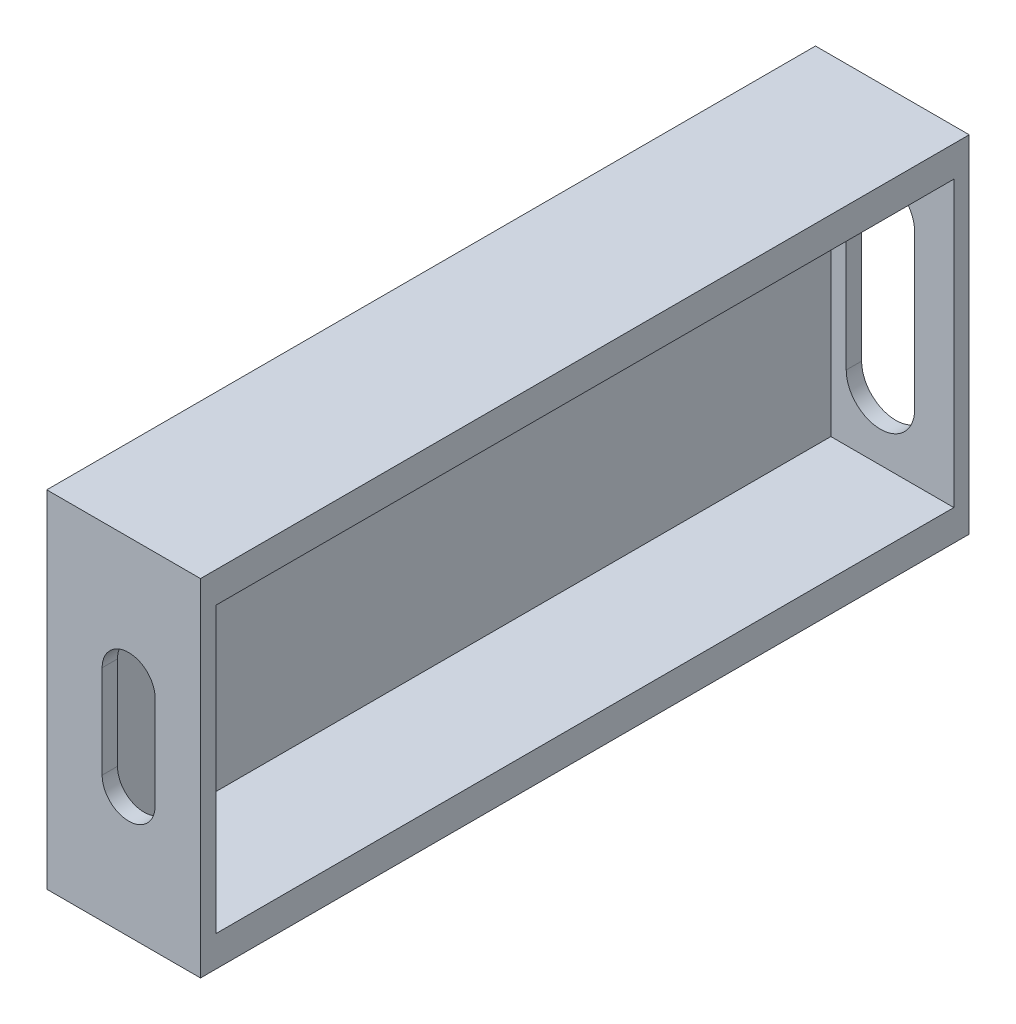
SolidWorks part; units mm, degrees
ref_plane "Front Plane" through (0, 0, 0) normal (0, 0, 1) x (1, 0, 0)
ref_plane "Top Plane" through (0, 0, 0) normal (0, 1, 0) x (1, 0, 0)
ref_plane "Right Plane" through (0, 0, 0) normal (1, 0, 0) x (0, 0, -1)
sketch "Sketch2" plane through (0, 0, 0) normal (1, 0, 0) x (0, 0, -1)
  line L1 (0, 0) -> (50, 0)
  line L2 (0, 0) -> (0, 22.5)
  line L3 (0, 22.5) -> (50, 22.5)
  line L4 (50, 0) -> (50, 22.5)
  dimension "D1" = 50
  dimension "D2" = 22.5
extrude "Boss-Extrude1" add sketch "Sketch2" along normal blind 10 contours L2 L3 L4 L1
sketch "Sketch4" plane through (0, 0, 0) normal (0, 0, 1) x (1, 0, 0)
  line L0 (5.325, 14.275) -> (5.325, 8.225) construction
  line L1 (7.05, 14.275) -> (7.05, 8.225)
  line L2 (3.6, 14.275) -> (3.6, 8.225)
  line L3 (0, 0) -> (0, 22.5) construction
  arc A0 (7.05, 14.275) -> (3.6, 14.275) centre (5.325, 14.275) ccw
  arc A1 (3.6, 8.225) -> (7.05, 8.225) centre (5.325, 8.225) ccw
  point P2 (5.325, 11.25)
  point P7 (3.6, 11.25)
  point P10 (0, 11.25)
  point P11 (5.325, 16)
  point P12 (5.325, 6.5)
  dimension "D3" = 3.45
  dimension "D4" = 9.5
  dimension "D1" = 0
  dimension "D2" = 3.6
extrude "USBC" cut sketch "Sketch4" against normal blind 10
sketch "Sketch5" plane through (0, 0, -50) normal (0, 0, -1) x (-1, 0, 0)
  line L0 (-5.225, 16.25) -> (-5.225, 6.25) construction
  line L1 (-3, 16.25) -> (-3, 6.25)
  line L2 (-7.45, 16.25) -> (-7.45, 6.25)
  line L3 (-10, 0) -> (-10, 22.5) construction
  line L5 (0, 0) -> (0, 22.5) construction
  arc A0 (-3, 16.25) -> (-7.45, 16.25) centre (-5.225, 16.25) ccw
  arc A1 (-7.45, 6.25) -> (-3, 6.25) centre (-5.225, 6.25) ccw
  point P2 (-5.225, 11.25)
  point P7 (-7.45, 11.25)
  point P10 (-10, 11.25)
  point P13 (-5.225, 4.025)
  point P14 (-5.225, 18.475)
  dimension "D4" = 14.45
  dimension "D3" = 4.45
  dimension "D1" = 0
  dimension "D2" = 3
extrude "POGO" cut sketch "Sketch5" against normal blind 10
sketch "Sketch6" plane through (10, 0, 0) normal (1, 0, 0) x (0, 0, -1)
  line L0 (0, 22.5) -> (50, 22.5) construction
  line L1 (1, 20.5) -> (49, 20.5)
  line L2 (1, 20.5) -> (1, 2)
  line L3 (1, 2) -> (49, 2)
  line L4 (49, 20.5) -> (49, 2)
  line L5 (0, 0) -> (0, 22.5) construction
  line L6 (0, 0) -> (50, 0) construction
  line L7 (50, 0) -> (50, 22.5) construction
  dimension "D1" = 2
  dimension "D2" = 1
  dimension "D3" = 2
  dimension "D4" = 1
extrude "Cut-Extrude3" cut sketch "Sketch6" against normal offset from surface (8 mm away) 2 up to face at (0, 11.25, -25)
